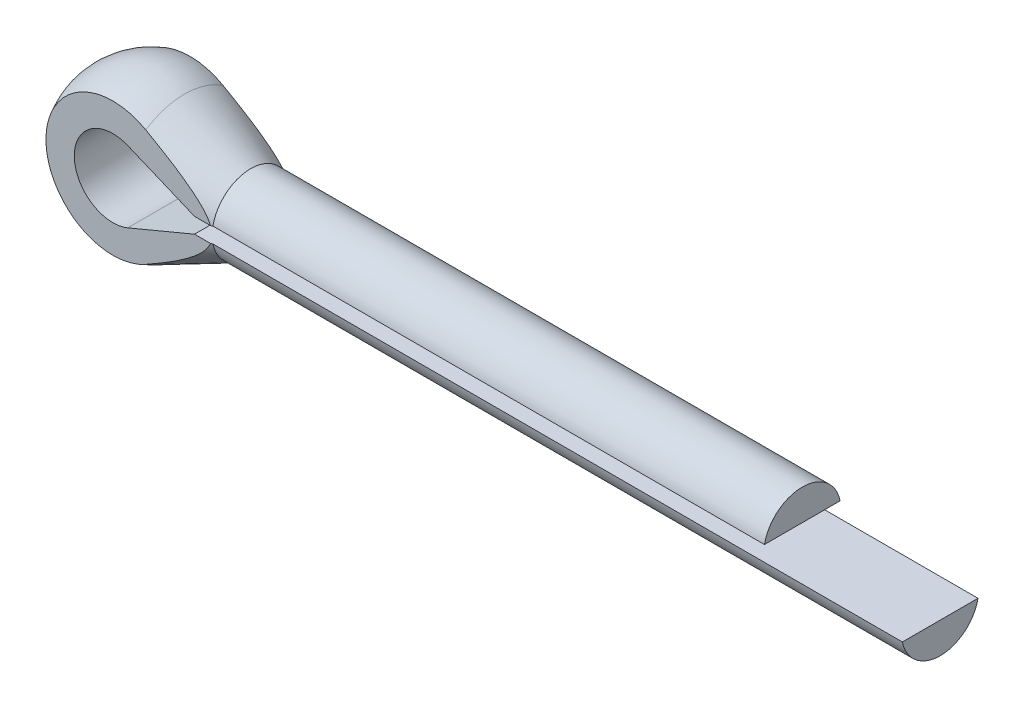
SolidWorks part; units mm, degrees
ref_plane "Front Plane" through (0, 0, 0) normal (0, 0, 1) x (1, 0, 0)
ref_plane "Top Plane" through (0, 0, 0) normal (0, 1, 0) x (1, 0, 0)
ref_plane "Right Plane" through (0, 0, 0) normal (1, 0, 0) x (0, 0, -1)
sketch "Sketch1" plane through (0, 0, 0) normal (0, 0, 1) x (1, 0, 0)
  line L3 (0, 0.7) -> (-1.2037, 1.2667)
  line L4 (12.5, 0.7) -> (0, 0.7)
  line L5 (12.5, 0) -> (12.5, 0.7)
  line L6 (0, 0) -> (12.5, 0) construction
  line L7 (-3.2, 0) -> (12.5, 0)
  arc A1 (-1.2037, 1.2667) -> (-3.2, 0) centre (-1.8, 0) ccw
  point P2 (10, 0)
  point P6 (-1.8, 1.4)
  dimension "SPP_B_s" = 3.2
  dimension "SPP_D_s" = 1.4
  dimension "SPP_C_s" = 2.8
  dimension "SPP_MSM_1" = 1.8
  dimension "SPP_A_s" = 2.5
  dimension "SPP_L" = 10
revolve "Revolve1" add sketch "Sketch1" angle 360 about L6
sketch "Sketch2" plane through (0, 0, 0) normal (0, 1, 0) x (1, 0, 0)
  line L2 (0, 0) -> (-1.8, 0) construction
  line L3 (-3.0124, 0.7) -> (0, 0.7)
  line L5 (-3.0124, -0.7) -> (0, -0.7)
  line L7 (0, -0.7) -> (0, 0.7) construction
  line L8 (-1.8, 1.4) -> (-1.8, -1.4) construction
  line L14 (-1.2037, -1.2667) -> (0, -0.7)
  line L15 (0, 0.7) -> (-1.2037, 1.2667)
  arc A1 (-1.2037, 1.2667) -> (-3.0124, 0.7) centre (-1.8, 0) ccw
  arc A2 (-3.0124, -0.7) -> (-1.2037, -1.2667) centre (-1.8, 0) ccw
  dimension "SPP_D_s" = 1.4
  dimension "SPP_MSM_1" = 1.8
  dimension "SPP_C_s" = 2.8
extrude "Cut-Extrude1" cut sketch "Sketch2" against normal through all and the other way through all
sketch "Sketch3" plane through (0, 0, 0) normal (0, 0, 1) x (1, 0, 0)
  line L0 (0, 0) -> (12.5, 0) construction
  line L1 (12.5, 0.7) -> (0, 0.7) construction
  line L11 (-1.53, 0.6458) -> (-0.32, 0.14)
  line L12 (-0.32, -0.14) -> (-1.53, -0.6458)
  line L13 (12.5, -0.14) -> (-0.32, -0.14)
  line L14 (10, 0.14) -> (-0.32, 0.14)
  line L19 (10, 0.14) -> (10, 0.7)
  line L20 (12.5, 0.7) -> (10, 0.7)
  line L21 (12.5, -0.14) -> (12.5, 0.7)
  line L23 (12.5, -0.7) -> (12.5, 0.7) construction
  arc A1 (-1.53, 0.6458) -> (-1.53, -0.6458) centre (-1.8, 0) ccw
  dimension "SPP_MSM_2" = 0.7
  dimension "SPP_MSM_3" = 0.32
  dimension "SPP_MSM_4" = 0.28
extrude "Cut-Extrude2" cut sketch "Sketch3" against normal through all and the other way through all
